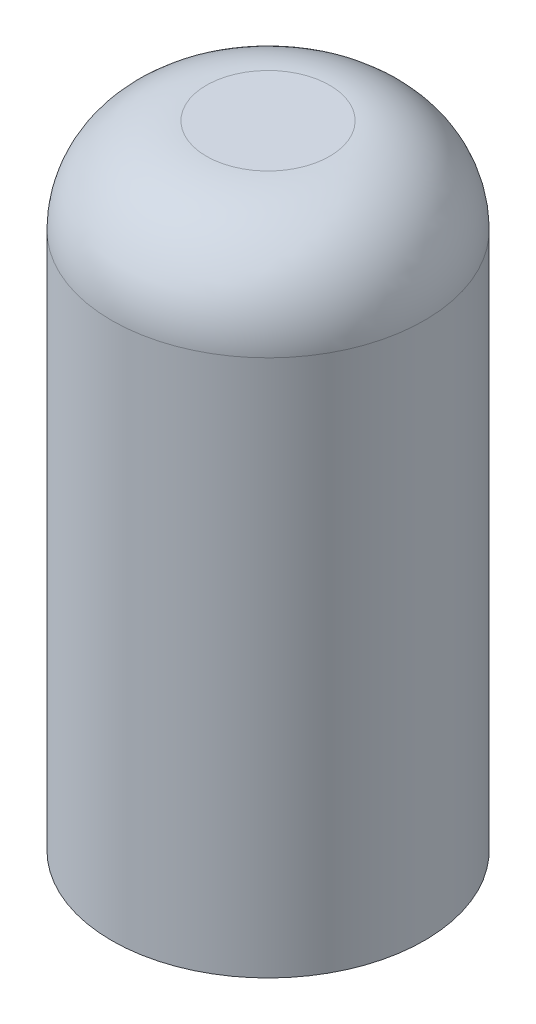
SolidWorks part; units mm, degrees
ref_plane "Front Plane" through (0, 0, 0) normal (0, 0, 1) x (1, 0, 0)
ref_plane "Top Plane" through (0, 0, 0) normal (0, 1, 0) x (1, 0, 0)
ref_plane "Right Plane" through (0, 0, 0) normal (1, 0, 0) x (0, 0, -1)
sketch "Sketch1" plane through (0, 0, 0) normal (0, 1, 0) x (1, 0, 0)
  circle A0 centre (0, 0) radius 4.95
  dimension "D1" = 9.9
extrude "Boss-Extrude1" add sketch "Sketch1" along normal blind 20
fillet "Fillet1" radius 3 1 edges at (0, 20, 4.95)
